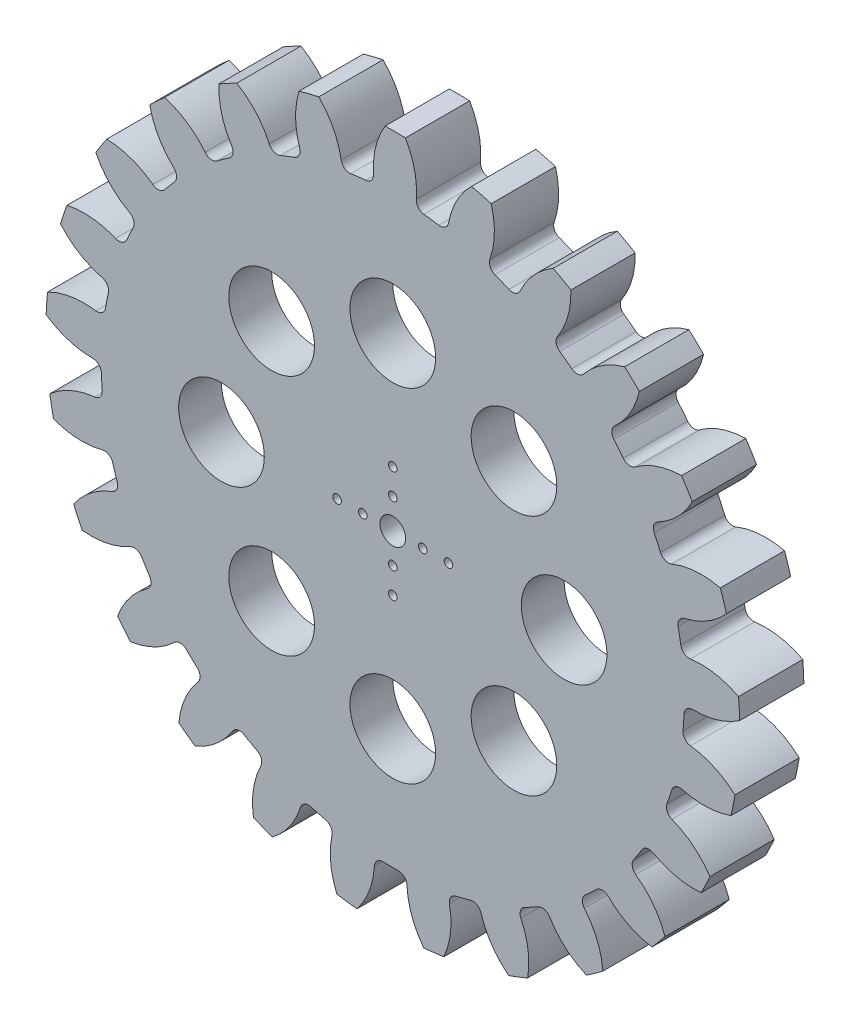
SolidWorks part; units mm, degrees
ref_plane "Front Plane" through (0, 0, 0) normal (0, 0, 1) x (1, 0, 0)
ref_plane "Top Plane" through (0, 0, 0) normal (0, 1, 0) x (1, 0, 0)
ref_plane "Right Plane" through (0, 0, 0) normal (1, 0, 0) x (0, 0, -1)
sketch "Basic Circles" plane through (0, 0, 0) normal (0, 0, 1) x (1, 0, 0)
  line L0 (0, 0) -> (0, 50000) construction
  line L2 (0, 0) -> (-50000, 0) construction
  circle A0 centre (0, 0) radius 68.058
  circle A1 centre (0, 0) radius 75
  circle A2 centre (0, 0) radius 81
sketch "Q-Circles" plane through (0, 0, 0) normal (0, 0, 1) x (1, 0, 0)
  line L0 (0, 0) -> (48.2091, 57.4533)
  line L1 (200000, 0) -> (-250000, 0) construction
  line L2 (0, -200000) -> (0, 250000) construction
  circle A0 centre (0, 0) radius 75 construction
  arc A1 (48.2091, 57.4533) -> (0, 0) centre (24.1045, 28.7267) cw construction
  arc A2 (36.1568, 43.09) -> (64.7633, 48.6489) centre (48.2091, 57.4533) ccw construction
  circle A3 centre (0, 0) radius 81 construction
  circle A4 centre (0, 0) radius 72.6184 construction
  point P3 (36.1568, 43.09)
  point P4 (48.2091, 57.4533)
  point P13 (59.1032, 42.1929)
  dimension "D3" = 18.75
  dimension "D2" = 37.5
sketch "Pressure Angle Circle" plane through (0, 0, 0) normal (0, 0, 1) x (1, 0, 0)
  line L0 (0, 0) -> (-13.0236, 73.8606)
  line L1 (0, -200000) -> (0, 250000) construction
  line L2 (34.5306, 68.9309) -> (61.8875, 45.9757) construction
  line L3 (15.042, 76.6023) -> (81.3761, 38.3043) construction
  line L4 (0, 0) -> (37.5, 64.9519)
  line L5 (0, 0) -> (48.2091, 57.4533) construction
  circle A0 centre (0, 0) radius 73.8606 construction
  circle A1 centre (0, 0) radius 75 construction
  point P10 (48.2091, 57.4533)
  point P11 (48.2091, 57.4533)
  point P16 (48.2091, 57.4533)
  point P18 (36.9303, 63.9651)
  dimension "D3" = 10
sketch "Pitch points" plane through (0, 0, 0) normal (0, 0, 1) x (1, 0, 0)
  line L0 (0, 0) -> (40.6321, 63.0399) construction
  line L1 (0, 0) -> (32.4107, 67.6354) construction
  circle A2 centre (0, 0) radius 75 construction
  circle A3 centre (0, 0) radius 75 construction
  point P1 (12.5058, 70.9056)
  point P4 (18.638, 69.5458)
  point P5 (24.6284, 67.6568)
  point P6 (30.4314, 65.2528)
  point P9 (36.0028, 62.3522)
  point P10 (40.6321, 63.0399)
  point P15 (32.4107, 67.6354)
  point P16 (23.6782, 71.1642)
  point P21 (14.5723, 73.5707)
  point P22 (5.2365, 74.817)
  point P23 (-4.1818, 74.8833)
  point P28 (-13.5342, 73.7687)
  point P29 (-22.6732, 71.4907)
  point P30 (-31.4546, 68.0853)
  point P31 (-39.7399, 63.6061)
  dimension "D2" = 7.2
  dimension "D1" = 9.42
  dimension "D3" = 10
sketch "Q-Circles (Even No Points)" plane through (0, 0, 0) normal (0, 0, 1) x (1, 0, 0)
  line L0 (0, 0) -> (-30.5449, 65.8821) construction
  line L1 (0, 0) -> (-13.2011, 71.4085) construction
  circle A0 centre (0, 0) radius 72.6184 construction
  circle A1 centre (0, 0) radius 72.6184 construction
  circle A3 centre (0, 0) radius 68.058 construction
  circle A4 centre (0, 0) radius 81 construction
  arc A5 (-49.7384, 63.9304) -> (-42.6448, 53.0407) centre (-31.4546, 68.0853) ccw
  arc A6 (-28.1144, 61.9796) -> (-32.277, 74.2913) centre (-13.5342, 73.7687) cw
  point P10 (-45.9695, 56.216)
  point P13 (-30.5449, 65.8821)
  point P15 (-13.2011, 71.4085)
  point P20 (4.9722, 72.448)
  point P23 (22.8331, 68.9354)
  point P24 (39.2593, 61.0913)
  dimension "D1" = 18.75
  dimension "D2" = 18.75
  dimension "D3" = 14.4
  dimension "D4" = 5
sketch "Q-Circles (Odd No Points)" plane through (0, 0, 0) normal (0, 0, 1) x (1, 0, 0)
  line L0 (0, 0) -> (-3.951, 72.5109) construction
  line L1 (0, 0) -> (14.2059, 71.2154) construction
  circle A0 centre (0, 0) radius 72.6184 construction
  circle A3 centre (0, 0) radius 72.6184 construction
  arc A5 (-21.0236, 64.7294) -> (-26.25, 76.6286) centre (-39.7399, 63.6061) ccw
  arc A6 (-4.2655, 67.9242) -> (-6.3685, 80.7493) centre (-22.6732, 71.4907) ccw
  circle A7 centre (0, 0) radius 68.058 construction
  circle A8 centre (0, 0) radius 81 construction
  point P14 (-3.951, 72.5109)
  point P17 (14.2059, 71.2154)
  point P21 (31.4701, 65.4452)
  point P22 (46.757, 55.5628)
  point P23 (-21.8596, 69.2503)
  point P24 (59.1059, 42.1892)
  dimension "D1" = 18.75
  dimension "D2" = 18.75
  dimension "D3" = 14.4
  dimension "D4" = 5
sketch "Gear Profile" plane through (0, 0, 0) normal (0, 0, 1) x (1, 0, 0)
  arc A1 (-28.1256, 61.9745) -> (-36.4185, 72.3512) centre (-45.9695, 56.216) ccw
  arc A5 (-36.4502, 57.4741) -> (-40.5905, 70.0957) centre (-21.8596, 69.2503) cw
  arc A6 (-11.8296, 67.022) -> (-17.2814, 79.135) centre (-30.5449, 65.8821) ccw
  arc A7 (-21.0118, 64.7333) -> (-21.8832, 77.988) centre (-3.951, 72.5109) cw
  circle A8 centre (0, 0) radius 68.058 construction
  circle A9 centre (0, 0) radius 81 construction
sketch "Sketch12" plane through (0, 0, 0) normal (0, 0, 1) x (1, 0, 0)
  circle A0 centre (0, 0) radius 68.058 construction
  circle A1 centre (0, 0) radius 68.058
extrude "Boss-Extrude2" add sketch "Sketch12" along normal mid plane 15
sketch "Sketch13" plane through (0, 0, 0) normal (0, 0, 1) x (1, 0, 0)
  circle A4 centre (0, 0) radius 68.058 construction
  circle A5 centre (0, 0) radius 81 construction
  arc A6 (-28.1256, 61.9745) -> (-36.4185, 72.3512) centre (-45.9695, 56.216) ccw construction
  arc A7 (-40.5905, 70.0957) -> (-36.4502, 57.4741) centre (-21.8596, 69.2503) ccw construction
  arc A8 (-28.1256, 61.9745) -> (-36.4502, 57.4741) centre (0, 0) ccw
  arc A9 (-36.4185, 72.3512) -> (-40.5905, 70.0957) centre (0, 0) ccw
  arc A10 (-28.1256, 61.9745) -> (-36.4185, 72.3512) centre (-45.9695, 56.216) ccw
  arc A11 (-40.5905, 70.0957) -> (-36.4502, 57.4741) centre (-21.8596, 69.2503) ccw
extrude "Boss-Extrude3" add sketch "Sketch13" along normal mid plane 15
fillet "Fillet1" radius 2 2 edges at (-36.4502, 57.4741, 0) (-28.1256, 61.9745, 0)
pattern_circular "CirPattern2" count 25 over 360 about axis through (0, 0, 0) along (0, 0, 1) of "Boss-Extrude3", "Fillet1"
sketch "Croquis1" plane through (0, 0, -7.5) normal (0, 0, -1) x (-1, 0, 0)
  line L0 (0, 0) -> (7, 0) construction
  line L1 (0, 0) -> (-7, 0) construction
  line L2 (7, 0) -> (13, 0) construction
  line L3 (-7, 0) -> (-13, 0) construction
  circle A0 centre (0, 0) radius 18 construction
  circle A1 centre (7, 0) radius 1
  circle A2 centre (13, 0) radius 1
  circle A3 centre (-7, 0) radius 1
  circle A4 centre (-13, 0) radius 1
  dimension "D1" = 36
  dimension "D3" = 2
  dimension "D5" = 2
  dimension "D8" = 2
  dimension "D9" = 2
  dimension "D2" = 7
  dimension "D4" = 6
  dimension "D6" = 7
  dimension "D7" = 6
extrude "Cortar-Extruir1" cut sketch "Croquis1" against normal blind 15
sketch "Croquis2" plane through (0, 0, -7.5) normal (0, 0, -1) x (-1, 0, 0)
  circle A0 centre (0, 0) radius 2
  dimension "D1" = 4
extrude "Cortar-Extruir2" cut sketch "Croquis2" against normal blind 15
sketch "Sketch14" plane through (0, 0, -7.5) normal (0, 0, -1) x (-1, 0, 0)
  line L0 (0, 0) -> (0, 7) construction
  line L1 (0, 7) -> (0, 13) construction
  line L2 (0, 0) -> (0, -7) construction
  line L3 (0, -7) -> (0, -13) construction
  circle A0 centre (0, 7) radius 1
  circle A1 centre (0, 13) radius 1
  circle A2 centre (0, -7) radius 1
  circle A3 centre (0, -13) radius 1
  dimension "D2" = 2
  dimension "D4" = 2
  dimension "D7" = 2
  dimension "D8" = 2
  dimension "D1" = 7
  dimension "D3" = 6
  dimension "D5" = 7
  dimension "D6" = 6
extrude "Cut-Extrude1" cut sketch "Sketch14" against normal blind 15
sketch "Sketch15" plane through (0, 0, -7.5) normal (0, 0, -1) x (-1, 0, 0)
  line L0 (0, 0) -> (0, 55) construction
  line L1 (0, 0) -> (-55, 0) construction
  line L2 (0, 0) -> (0, -55) construction
  line L3 (0, 0) -> (55, 0) construction
  line L4 (0, 0) -> (-38.8909, 38.8909) construction
  line L5 (0, 0) -> (-38.8909, -38.8909) construction
  line L6 (0, 0) -> (38.8909, -38.8909) construction
  line L7 (0, 0) -> (38.8909, 38.8909) construction
  circle A0 centre (0, 0) radius 17.5 construction
  circle A1 centre (0, 40) radius 10
  circle A2 centre (28.2843, 28.2843) radius 10
  circle A3 centre (40, 0) radius 10
  circle A4 centre (28.2843, -28.2843) radius 10
  circle A5 centre (0, -40) radius 10
  circle A6 centre (-28.2843, -28.2843) radius 10
  circle A7 centre (-40, 0) radius 10
  circle A8 centre (-28.2843, 28.2843) radius 10
  dimension "D1" = 35
  dimension "D4" = 20
  dimension "D5" = 20
  dimension "D6" = 20
  dimension "D13" = 20
  dimension "D14" = 20
  dimension "D15" = 20
  dimension "D16" = 20
  dimension "D17" = 20
  dimension "D2" = 40
  dimension "D3" = 40
  dimension "D7" = 40
  dimension "D8" = 40
  dimension "D9" = 40
  dimension "D10" = 40
  dimension "D11" = 40
  dimension "D12" = 40
extrude "Cut-Extrude2" cut sketch "Sketch15" against normal blind 25
sketch "Sketch16" plane through (0, 0, -7.5) normal (0, 0, -1) x (-1, 0, 0)
  circle A0 centre (0, 0) radius 20
  circle A1 centre (0, 0) radius 57.5
  dimension "D1" = 40
  dimension "D2" = 115
extrude "Cut-Extrude3" cut sketch "Sketch16" against normal blind 5
sketch "Sketch17" plane through (0, 0, 7.5) normal (0, 0, 1) x (1, 0, 0)
  circle A0 centre (0, 0) radius 3
  dimension "D1" = 6
extrude "Cut-Extrude4" cut sketch "Sketch17" against normal blind 15
equation "\"module\"= 6"
equation "\"no of teeth\"= 25"
equation "\"addendum\"= \"module\" * 1"
equation "\"clearence\"= \"module\" * .157"
equation "\"dedendum\"= \"addendum\" + \"clearence\""
equation "\"circular pitch\"= \"module\" * 3.14"
equation "\"D1@Basic Circles\" = \"module\" * \"no of teeth\""
equation "\"D2@Basic Circles\"= \"D1@Basic Circles\" + 2 * \"addendum\""
equation "\"D3@Basic Circles\" = \"D1@Basic Circles\" - 2 * \"dedendum\""
equation "\"D3@Q-Circles\"= \"module\" * \"no of teeth\" / 8"
equation "\"D1@Boss-Extrude2\"=\"module\"*2.5"
equation "\"D1@Boss-Extrude3\"=\"module\"*2.5"
equation "\"D1@Pitch points\"   = \"circular pitch\" / 2"
equation "\"D2@Pitch points\"   = ( \"D1@Pitch points\" * 360 ) / ( 3.14 * \"module\" * \"no of teeth\" )"
equation "\"D1@Q-Circles (Even No Points)\"= \"module\" * \"no of teeth\" / 8"
equation "\"D2@Q-Circles (Even No Points)\" = \"module\" * \"no of teeth\" / 8"
equation "\"D3@Q-Circles (Even No Points)\" = ( \"circular pitch\" / 2 * 360 ) / ( \"module\" * \"no of teeth\" * 3.14 ) * 2"
equation "\"D1@Q-Circles (Odd No Points)\"   = \"module\" * \"no of teeth\" / 8"
equation "\"D2@Q-Circles (Odd No Points)\"   = \"module\" * \"no of teeth\" / 8"
equation "\"D3@Q-Circles (Odd No Points)\" = ( \"circular pitch\" / 2 * 360 ) / ( \"module\" * \"no of teeth\" * 3.14 ) * 2"
equation "\"D1@CirPattern2\" = \"no of teeth\""
equation "\"Pressure Angle\"= 10deg"
equation "\"D2@Pressure Angle Circle\" = \"Pressure Angle\""
equation "\"D3@Pressure Angle Circle\" = \"Pressure Angle\""
equation "\"D1@Pressure Angle Circle\" = \"Pressure Angle\""
